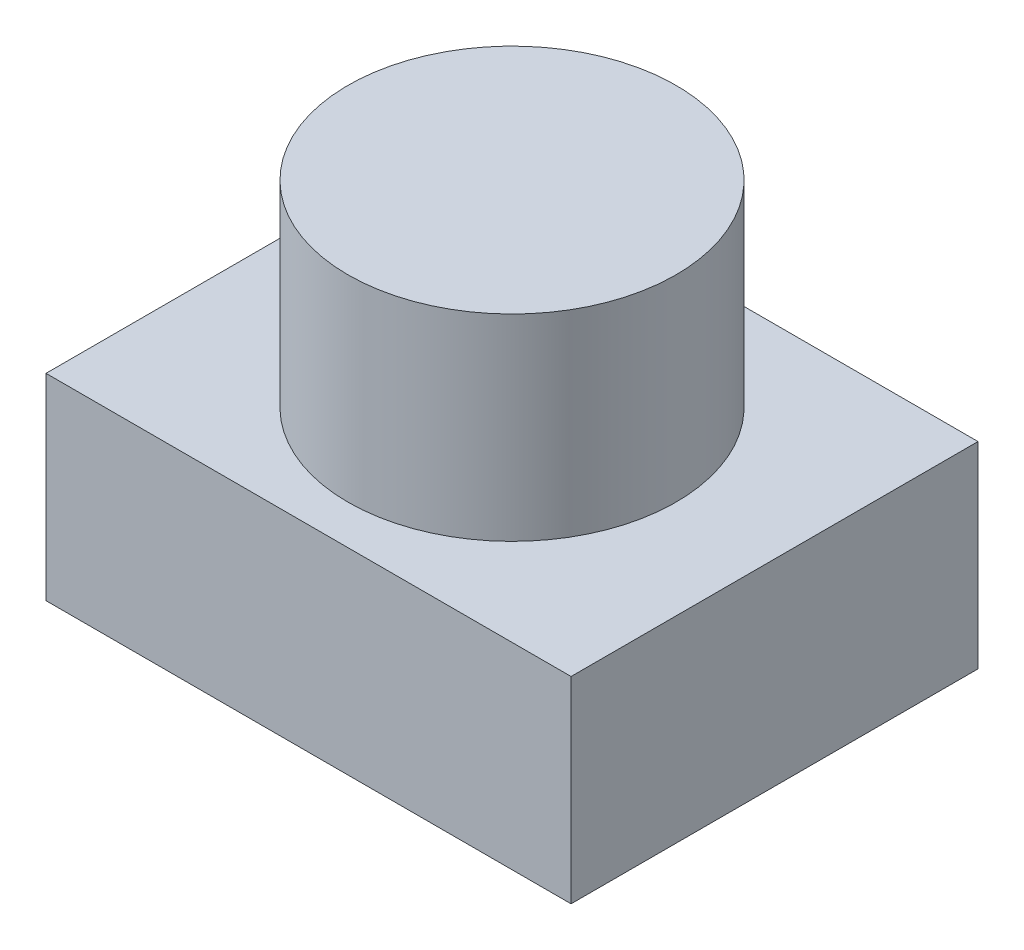
SolidWorks part; units mm, degrees
ref_plane "Front Plane" through (0, 0, 0) normal (0, 0, 1) x (1, 0, 0)
ref_plane "Top Plane" through (0, 0, 0) normal (0, 1, 0) x (1, 0, 0)
ref_plane "Right Plane" through (0, 0, 0) normal (1, 0, 0) x (0, 0, -1)
sketch "草图1" plane through (0, 0, 0) normal (0, 1, 0) x (1, 0, 0)
  line L1 (-20, -15.5) -> (20, -15.5)
  line L2 (-20, -15.5) -> (-20, 15.5)
  line L3 (-20, 15.5) -> (20, 15.5)
  line L4 (20, -15.5) -> (20, 15.5)
  line L5 (-20, -15.5) -> (20, 15.5) construction
  line L6 (-20, 15.5) -> (20, -15.5) construction
  point P0 (0, 0)
  dimension "D1" = 31
  dimension "D2" = 40
extrude "凸台-拉伸1" add sketch "草图1" along normal blind 15
sketch "草图2" plane through (0, 15, 0) normal (0, 1, 0) x (1, 0, 0)
  circle A0 centre (0, 0) radius 12.5
  dimension "D1" = 25
extrude "凸台-拉伸2" add sketch "草图2" along normal blind 15
